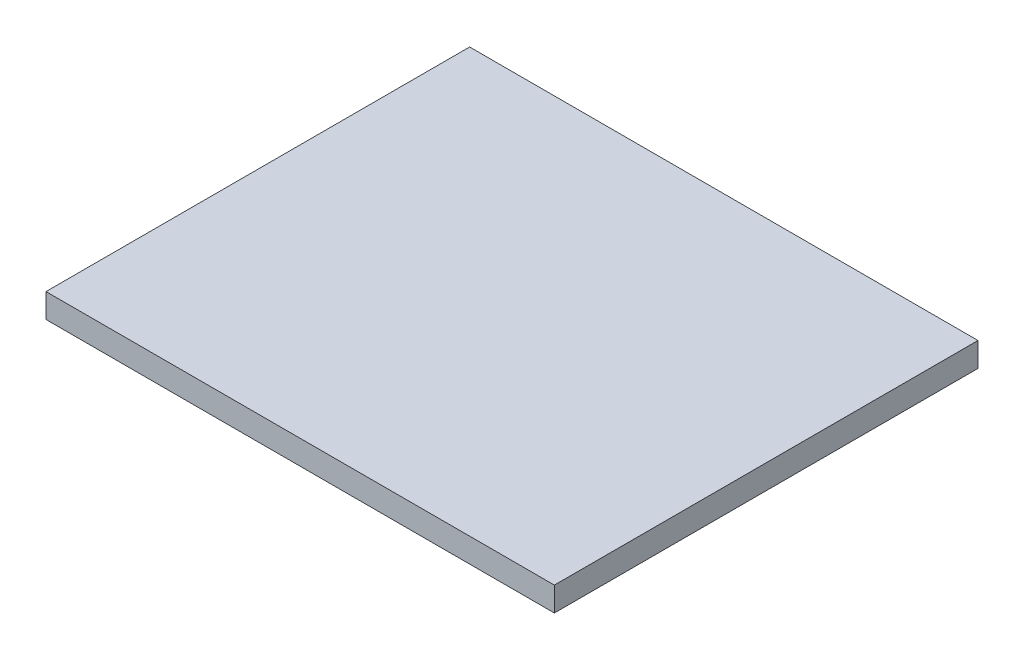
SolidWorks part; units mm, degrees
material "Glass"
ref_plane "Front Plane" through (0, 0, 0) normal (0, 0, 1) x (1, 0, 0)
ref_plane "Top Plane" through (0, 0, 0) normal (0, 1, 0) x (1, 0, 0)
ref_plane "Right Plane" through (0, 0, 0) normal (1, 0, 0) x (0, 0, -1)
sketch "Sketch1" plane through (0, 0, 0) normal (0, 1, 0) x (1, 0, 0)
  line L0 (0, 37.0077) -> (0, -43.1852) construction
  line L1 (57.5422, 0) -> (-54.911, 0) construction
  line L3 (21, 17.5) -> (-21, 17.5)
  line L4 (21, 17.5) -> (21, -17.5)
  line L5 (21, -17.5) -> (-21, -17.5)
  line L6 (-21, 17.5) -> (-21, -17.5)
  line L7 (21, 17.5) -> (-21, -17.5) construction
  line L8 (21, -17.5) -> (-21, 17.5) construction
  point P5 (0, 0)
  dimension "D1" = 42
  dimension "D2" = 35
extrude "Boss-Extrude1" add sketch "Sketch1" along normal blind 2
